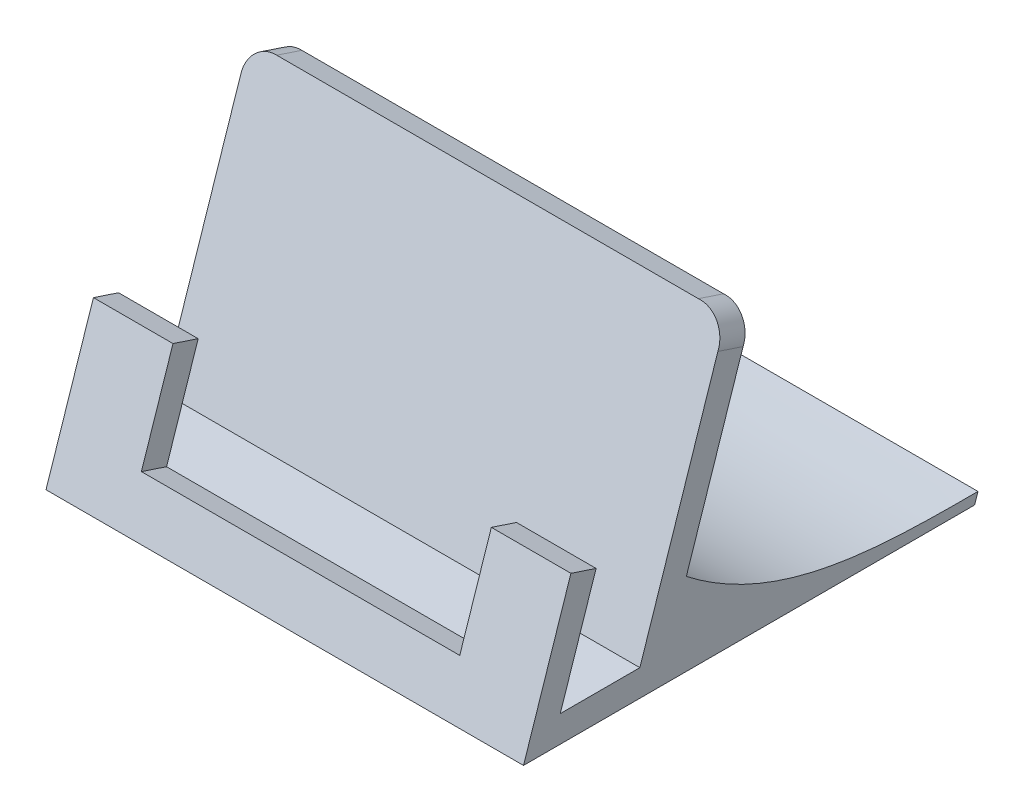
SolidWorks part; units mm, degrees
ref_plane "Front Plane" through (0, 0, 0) normal (0, 0, 1) x (1, 0, 0)
ref_plane "Top Plane" through (0, 0, 0) normal (0, 1, 0) x (1, 0, 0)
ref_plane "Right Plane" through (0, 0, 0) normal (1, 0, 0) x (0, 0, -1)
sketch "Sketch1" plane through (0, 0, 0) normal (0, 1, 0) x (1, 0, 0)
  line L1 (-441.4449, -349.7338) -> (-351.4449, -349.7338)
  line L2 (-441.4449, -349.7338) -> (-441.4449, -439.7338)
  line L3 (-441.4449, -439.7338) -> (-351.4449, -439.7338)
  line L4 (-351.4449, -349.7338) -> (-351.4449, -439.7338)
  dimension "D1" = 90
  dimension "D2" = 90
extrude "Boss-Extrude1" add sketch "Sketch1" along normal blind 25
sketch "Sketch2" plane through (-351.4449, 0, 0) normal (1, 0, 0) x (0, 0, -1)
  line L1 (-349.7338, 25) -> (-299.7338, 25)
  line L2 (-349.7338, 25) -> (-349.7338, 0)
  line L3 (-349.7338, 0) -> (-299.7338, 0)
  line L4 (-299.7338, 25) -> (-299.7338, 0)
  dimension "D1" = 50
extrude "Boss-Extrude2" add sketch "Sketch2" against normal blind 90
sketch "Sketch3" plane through (-351.4449, 0, 0) normal (1, 0, 0) x (0, 0, -1)
  line L0 (-439.7338, 0) -> (-431.4286, 25)
  line L1 (-439.7338, 25) -> (-299.7338, 25) construction
  line L2 (-431.4286, 25) -> (-426.6836, 23.4237)
  line L3 (-432.8041, 5) -> (-422.8041, 5)
  line L4 (-422.8041, 5) -> (-417.8041, 5)
  line L6 (-417.8041, 5) -> (-409.8698, 28.8836)
  line L7 (-432.8041, 5) -> (-426.6836, 23.4237)
  line L8 (-409.8698, 28.8836) -> (-456.5569, 33.3478)
  line L9 (-456.5569, 33.3478) -> (-439.7338, 0)
extrude "Cut-Extrude1" cut sketch "Sketch3" against normal blind 114
sketch "Sketch6" plane through (-351.4449, 0, 0) normal (1, 0, 0) x (0, 0, -1)
  line L0 (-417.8041, 5) -> (-402.0369, 52.4489)
  line L1 (-402.0369, 52.4489) -> (-397.292, 50.8721)
  line L2 (-397.292, 50.8721) -> (-412.9583, 3.7269)
  line L3 (-412.9583, 3.7269) -> (-417.8041, 5)
extrude "Boss-Extrude3" add sketch "Sketch6" against normal blind 90
sketch "Sketch8" plane through (-441.4449, 0, 0) normal (-1, 0, 0) x (0, 0, 1)
  line L0 (402.0369, 52.4489) -> (417.8041, 5)
  line L1 (417.8041, 5) -> (422.6678, 11.8435)
  line L2 (422.6678, 11.8435) -> (408.0964, 67.2044)
  line L3 (408.0964, 67.2044) -> (402.0369, 52.4489)
extrude "Cut-Extrude2" cut sketch "Sketch8" against normal blind 90
sketch "Sketch11" plane through (0, 131.5636, 396.0273) normal (0, 0.3153, 0.949) x (1, 0, 0)
  line L0 (-396.4449, -112.29) -> (-366.4449, -112.29)
  line L1 (-441.4449, -112.29) -> (-351.4449, -112.29) construction
  line L3 (-396.4449, -112.29) -> (-426.4449, -112.29)
  line L4 (-426.4449, -112.29) -> (-426.4449, -132.29)
  line L5 (-366.4449, -112.29) -> (-366.4449, -132.29)
  line L6 (-426.4449, -132.29) -> (-366.4449, -132.29)
  line L7 (-366.4449, -132.29) -> (-366.5467, -132.5565)
extrude "Cut-Extrude3" cut sketch "Sketch11" against normal blind 7 contours L6 L4 L3 L0 L5
sketch "Sketch12" plane through (0, 131.5636, 396.0273) normal (0, 0.3153, 0.949) x (1, 0, 0)
  line L0 (-426.4449, -132.29) -> (-426.4449, -136.0528)
  line L1 (-426.4449, -136.0528) -> (-366.4449, -136.0528)
  line L2 (-366.4449, -136.0528) -> (-366.4449, -132.29)
  line L3 (-366.4449, -132.29) -> (-426.4449, -132.29)
  line L4 (-426.4449, -132.29) -> (-426.6836, -132.3147)
  line M2 (-366.4449, -132.29) -> (-426.4449, -132.29)
extrude "Cut-Extrude4" cut sketch "Sketch12" against normal blind 7 contours L1 L2 L0 M2
sketch "Sketch13" plane through (0, 5, 0) normal (0, 1, 0) x (1, 0, 0)
  line L0 (-426.4449, -430.6966) -> (-426.4449, -437.2944)
  line L1 (-426.4449, -437.2944) -> (-366.4449, -437.2944)
  line L2 (-366.4449, -437.2944) -> (-366.4449, -430.6966)
  line L3 (-366.4449, -430.6966) -> (-426.4449, -430.6966)
extrude "Boss-Extrude4" add sketch "Sketch13" against normal blind 4
sketch "Sketch15" plane through (0, 131.5636, 396.0273) normal (0, 0.3153, 0.949) x (1, 0, 0)
  line L0 (-366.4449, -131.1773) -> (-427.999, -131.1773)
  line L1 (-366.4449, -112.29) -> (-366.4449, -136.0528) construction
  line L2 (-427.999, -131.1773) -> (-427.999, -137.0127)
  line L3 (-427.999, -137.0127) -> (-362.6036, -137.0127)
  line L4 (-362.6036, -137.0127) -> (-366.4449, -131.1773)
  line L5 (-366.4449, -131.1773) -> (-366.3121, -131.139)
  line M1 (-366.4449, -136.0528) -> (-426.4449, -136.0528)
  line M2 (-426.4449, -136.0528) -> (-426.4449, -112.29)
  line M8 (-366.4449, -112.29) -> (-366.4449, -136.0528)
extrude "Boss-Extrude5" add sketch "Sketch15" against normal blind 6 contours L0 M8 M2 M1
sketch "Sketch16" plane through (-441.4449, 0, 0) normal (-1, 0, 0) x (0, 0, 1)
  line L0 (397.292, 50.8721) -> (405.8893, 25)
  line L1 (405.8893, 25) -> (409.6734, 13.6123)
  line L2 (409.6734, 13.6123) -> (299.7338, 13.6123)
  line L3 (299.7338, 0) -> (299.7338, 25) construction
  line L4 (299.7338, 13.6123) -> (299.7338, -6.3757)
  line L5 (299.7338, -6.3757) -> (282.5198, 35.689)
  line L6 (282.5198, 35.689) -> (320.9389, 45.9247)
  line L7 (320.9389, 45.9247) -> (405.8893, 25)
  line M5 (405.8893, 25) -> (299.7338, 25)
  line M6 (299.7338, 25) -> (299.7338, 0)
extrude "Cut-Extrude5" cut sketch "Sketch16" against normal blind 105 contours L7 L6 L5 L4 M6 M5 | L2 L1 M5 M6
sketch "Sketch17" plane through (-351.4449, 0, 0) normal (1, 0, 0) x (0, 0, -1)
  line L0 (-354.7036, 13.6123) -> (-354.7036, -9.1418)
  line L1 (-409.6734, 13.6123) -> (-299.7338, 13.6123) construction
  line L2 (-354.7036, -9.1418) -> (-285.7103, -9.1418)
  line L3 (-285.7103, -9.1418) -> (-285.7103, 26.6616)
  line L4 (-285.7103, 26.6616) -> (-354.7036, 26.6616)
  line L5 (-354.7036, 26.6616) -> (-354.7036, 13.6123)
  line L6 (-354.7036, 13.6123) -> (-353.8831, 12.4531)
extrude "Cut-Extrude6" cut sketch "Sketch17" against normal blind 105
sketch "Sketch18" plane through (0, 125.5269, 377.7531) normal (0, 0.3153, 0.949) x (1, 0, 0)
  line L0 (-441.4449, -77.0072) -> (-436.4449, -77.0072)
  line L1 (-441.4449, -77.0072) -> (-351.4449, -77.0072) construction
  line L2 (-441.4449, -77.0072) -> (-441.4449, -82.0072)
  line L3 (-441.4449, -77.0072) -> (-441.4449, -127.0072) construction
  line L4 (-441.4449, -82.0072) -> (-436.4449, -77.0072)
extrude "Cut-Extrude7" cut sketch "Sketch18" against normal blind 105
sketch "Sketch19" plane through (0, 125.5269, 377.7531) normal (0, 0.3153, 0.949) x (1, 0, 0)
  line L0 (-351.4449, -77.0072) -> (-356.4449, -77.0072)
  line L1 (-436.4449, -77.0072) -> (-351.4449, -77.0072) construction
  line L2 (-351.4449, -77.0072) -> (-351.4449, -82.0072)
  line L3 (-351.4449, -77.0072) -> (-351.4449, -127.0072) construction
  line L4 (-356.4449, -77.0072) -> (-351.4449, -82.0072)
  line L5 (-351.4449, -82.0072) -> (-351.4875, -82.0138)
  line M4 (-351.4449, -127.0072) -> (-351.4449, -77.0072)
  line M5 (-351.4449, -77.0072) -> (-436.4449, -77.0072)
extrude "Cut-Extrude8" cut sketch "Sketch19" against normal blind 105 contours L4 M5 M4
sketch "Sketch20" plane through (0, 125.5269, 377.7531) normal (0, 0.3153, 0.949) x (1, 0, 0)
  circle A0 centre (-436.4449, -82.0072) radius 5.0024
extrude "Boss-Extrude6" add sketch "Sketch20" against normal blind 5
sketch "Sketch21" plane through (0, 125.5269, 377.7531) normal (0, 0.3153, 0.949) x (1, 0, 0)
  circle A0 centre (-356.4449, -82.0072) radius 5.0132
extrude "Boss-Extrude7" add sketch "Sketch21" against normal blind 5
sketch "Sketch22" plane through (-441.4449, 0, 0) normal (-1, 0, 0) x (0, 0, 1)
  line L0 (352.2867, 0) -> (351.9256, 18.9952)
  line L1 (351.9256, 18.9952) -> (405.5631, 20.0149)
  line L2 (405.5631, 20.0149) -> (409.6734, 13.6123)
  spline S0 degree 3 poles (409.6734, 13.6123) (391.6939, -0.3481) (371.9682, 0.0066) (352.2867, 0) knots 0 0 0 0 1 1 1 1
extrude "Cut-Extrude9" cut sketch "Sketch22" against normal blind 110
sketch "Sketch23" plane through (-351.4449, 0, 0) normal (1, 0, 0) x (0, 0, -1)
  line L0 (-432.2078, 6.795) -> (-432.8041, 5)
  line L1 (-426.6836, 23.4237) -> (-432.8041, 5) construction
  line L2 (-432.8041, 5) -> (-433.4346, 3.102)
  line L3 (-417.3099, 6.4873) -> (-417.8041, 5)
  line L4 (-403.7284, 47.3584) -> (-417.8041, 5) construction
  line L5 (-417.8041, 5) -> (-418.4348, 3.102)
  line L6 (-418.4348, 3.102) -> (-433.4346, 3.102)
  line L7 (-432.2078, 6.795) -> (-417.3099, 6.4873)
extrude "Cut-Extrude10" cut sketch "Sketch23" against normal blind 110
sketch "Sketch24" plane through (-351.4449, 0, 0) normal (1, 0, 0) x (0, 0, -1)
  line L0 (-437.6546, 6.2589) -> (-439.7338, 0)
  line L1 (-439.7338, 0) -> (-431.4286, 25) construction
  line L2 (-439.7338, 0) -> (-440.3644, -1.898)
  line L3 (-354.7036, 0) -> (-355.3342, -1.898)
  line L4 (-440.3644, -1.898) -> (-355.3342, -1.898)
  line L13 (-403.7284, 47.3584) -> (-418.4348, 3.102)
  line L14 (-418.4348, 3.102) -> (-433.4346, 3.102)
  line L15 (-433.4346, 3.102) -> (-426.6836, 23.4237)
  line L16 (-426.6836, 23.4237) -> (-431.4286, 25)
  line L17 (-431.4286, 25) -> (-439.7338, 0)
  line L18 (-439.7338, 0) -> (-354.7036, 0)
  line L19 (-409.6734, 13.6123) -> (-398.9836, 45.7817)
  line L20 (-398.9836, 45.7817) -> (-403.7284, 47.3584)
  line L25 (-437.6546, 6.2589) -> (-439.7338, 0)
  line L26 (-439.7338, 0) -> (-354.7036, 0)
  spline S1 degree 3 poles (-234.2391, -992.7169) (-152.1966, 999.0187) (-557.571, -1005.3227) (-472.4528, 1011.6286) knots -4.049869 -4.049869 -4.049869 -4.049869 4.124814 4.124814 4.124814 4.124814 only from (-354.7036, 0) to (-409.6734, 13.6123)
  line M15 (-439.7338, 0) -> (-354.7036, 0)
  dimension "D1" = 0
extrude "Boss-Extrude8" add sketch "Sketch24" against normal blind 90 contours L2 L4 L3 M15
